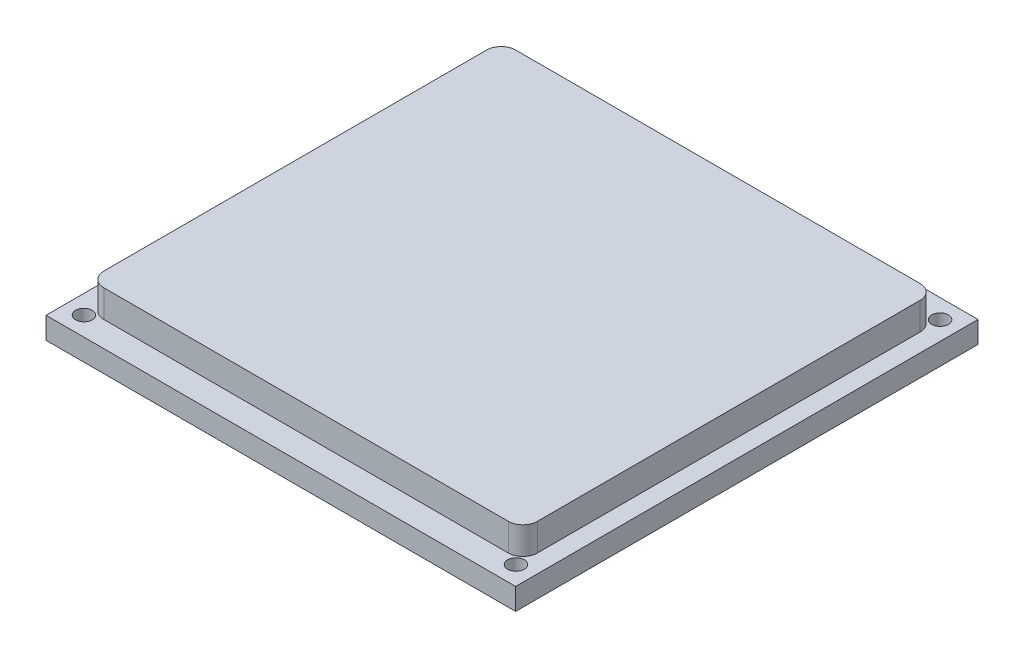
SolidWorks part; units mm, degrees
ref_plane "Front Plane" through (0, 0, 0) normal (0, 0, 1) x (1, 0, 0)
ref_plane "Top Plane" through (0, 0, 0) normal (0, 1, 0) x (1, 0, 0)
ref_plane "Right Plane" through (0, 0, 0) normal (1, 0, 0) x (0, 0, -1)
sketch "Sketch1" plane through (0, 0, 0) normal (0, 1, 0) x (1, 0, 0)
  line L0 (-68.3044, -14.3301) -> (38.4439, -14.3301) construction
  line L1 (-34.835, 17.6699) -> (30.165, 17.6699)
  line L2 (-34.835, 17.6699) -> (-34.835, -46.3301)
  line L3 (-34.835, -46.3301) -> (30.165, -46.3301)
  line L4 (30.165, 17.6699) -> (30.165, -46.3301)
  line L5 (-2.335, 26.4809) -> (-2.335, -56.1672) construction
  circle A0 centre (-32.235, 15.0199) radius 1.15
  circle A1 centre (27.565, 15.0199) radius 1.15
  circle A2 centre (-32.235, -43.6801) radius 1.15
  circle A3 centre (27.565, -43.6801) radius 1.15
  dimension "D4" = 2.3
  dimension "D1" = 65
  dimension "D2" = 64
  dimension "D3" = 58.7
  dimension "D5" = 59.8
extrude "Boss-Extrude1" add sketch "Sketch1" along normal blind 3
sketch "Sketch2" plane through (0, 3, 0) normal (0, 1, 0) x (1, 0, 0)
  line L0 (-2.335, 24.1188) -> (-2.335, -51.8182) construction
  line L1 (-30.335, 14.1699) -> (25.665, 14.1699)
  line L2 (-32.335, 12.1699) -> (-32.335, -40.8301)
  line L3 (-30.335, -42.8301) -> (25.665, -42.8301)
  line L4 (27.665, 12.1699) -> (27.665, -40.8301)
  line L5 (-34.835, 17.6699) -> (-34.835, -46.3301) construction
  line L6 (30.165, -46.3301) -> (30.165, 17.6699) construction
  line L7 (-52.0342, -14.3301) -> (45.2419, -14.3301) construction
  line L8 (30.165, 17.6699) -> (-34.835, 17.6699) construction
  line L9 (-34.835, -46.3301) -> (30.165, -46.3301) construction
  arc A0 (-30.335, 14.1699) -> (-32.335, 12.1699) centre (-30.335, 12.1699) ccw
  arc A1 (27.665, 12.1699) -> (25.665, 14.1699) centre (25.665, 12.1699) ccw
  arc A2 (25.665, -42.8301) -> (27.665, -40.8301) centre (25.665, -40.8301) ccw
  arc A3 (-32.335, -40.8301) -> (-30.335, -42.8301) centre (-30.335, -40.8301) ccw
  dimension "D3" = 4
  dimension "D4" = 4
  dimension "D5" = 4
  dimension "D6" = 4
  dimension "D1" = 57
  dimension "D2" = 60
extrude "Boss-Extrude2" add sketch "Sketch2" along normal blind 3.8
